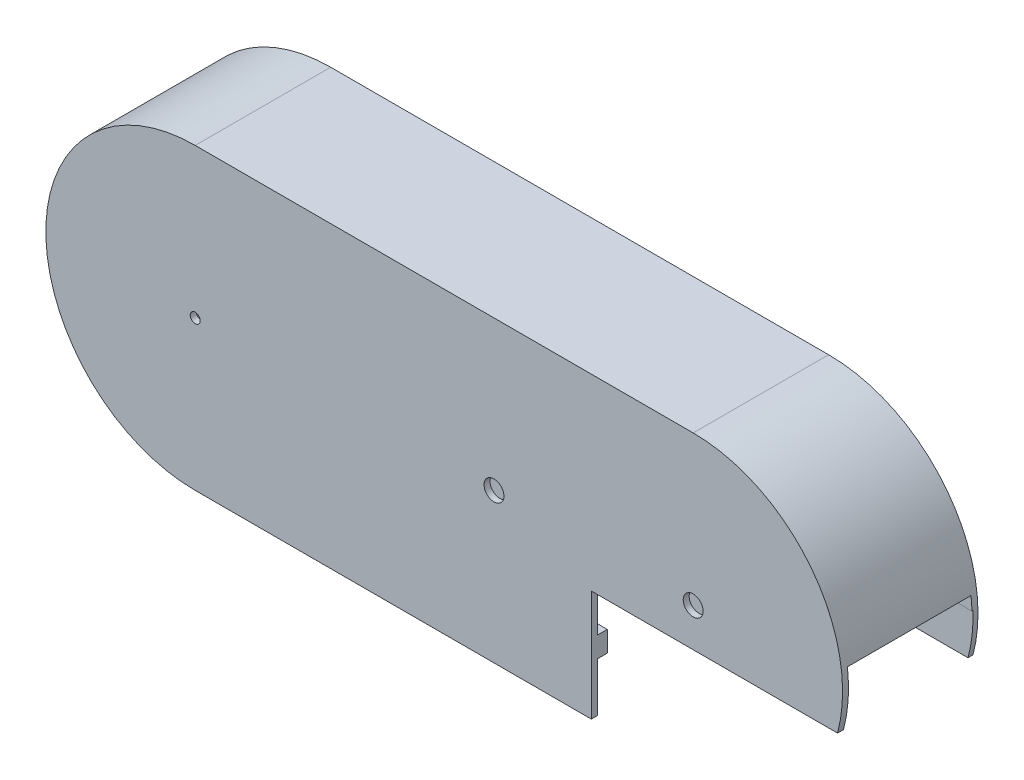
SolidWorks part; units mm, degrees
ref_plane "前视基准面" through (0, 0, 0) normal (0, 0, 1) x (1, 0, 0)
ref_plane "上视基准面" through (0, 0, 0) normal (0, 1, 0) x (1, 0, 0)
ref_plane "右视基准面" through (0, 0, 0) normal (1, 0, 0) x (0, 0, -1)
other "Configuration Table"
sketch "草图1" plane through (0, 0, 0) normal (0, 0, 1) x (1, 0, 0)
  line L0 (0, 0) -> (250, 0) construction
  line L1 (0, 75) -> (250, 75)
  line L2 (0, -75) -> (250, -75)
  arc A0 (0, 75) -> (0, -75) centre (0, 0) ccw
  arc A1 (250, -75) -> (250, 75) centre (250, 0) ccw
  point P3 (125, 0)
  dimension "D2" = 75
  dimension "D1" = 250
extrude "凸台-拉伸1" add sketch "草图1" along normal blind 68
ref_plane "基准面1" through (0, 0, 65) normal (0, 0, 1) x (1, 0, 0)
sketch "草图2" plane through (0, 0, 65) normal (0, 0, 1) x (1, 0, 0)
  line L0 (0, 75) -> (0, -75)
  line L1 (0, 0) -> (250, 0) construction
  line L2 (0, 72) -> (250, 72)
  line L3 (0, -72) -> (250, -72)
  arc A0 (0, 72) -> (0, -72) centre (0, 0) ccw
  arc A1 (250, -72) -> (250, 72) centre (250, 0) ccw
  point P7 (125, 0)
  dimension "D2" = 72
  dimension "D1" = 250
extrude "切除-拉伸2" cut sketch "草图2" against normal blind 62
ref_plane "基准面2" through (0, -75, 0) normal (0, -1, 0) x (-1, 0, 0)
sketch "草图3" plane through (0, -75, 0) normal (0, -1, 0) x (-1, 0, 0)
  line L0 (-82.5, -65) -> (82.5, -65) construction
  line L1 (-250, 0) -> (0, 0)
  line L2 (-250, 0) -> (-250, -65)
  line L3 (-250, -65) -> (0, -65)
  line L4 (0, 0) -> (0, -65)
  line L5 (0, -68) -> (0, 0) construction
extrude "切除-拉伸3" cut sketch "草图3" against normal blind 3
sketch "草图4" plane through (0, 0, 65) normal (0, 0, 1) x (1, 0, 0)
  line L0 (0, 75) -> (0, -75)
  line L1 (-1.65, -75) -> (1.65, -75) construction
  circle A0 centre (0, 0) radius 2.5
  dimension "D1" = 5
extrude "切除-拉伸5" cut sketch "草图4" against normal through all both and the other way through all contours L0 A0 | L0 A0
sketch "草图5" plane through (0, 0, 65) normal (0, 0, 1) x (1, 0, 0)
  line L1 (61.3786, 0) -> (220.7131, 0) construction
  line L2 (250, 75) -> (250, -75) construction
  line L3 (-1.65, -75) -> (1.65, -75) construction
  arc A0 (250, -75) -> (250, 75) centre (250, 0) ccw construction
  circle A1 centre (250, 0) radius 5
  circle A2 centre (150, 0) radius 5
  dimension "D1" = 10
  dimension "D2" = 10
  dimension "D3" = 100
extrude "切除-拉伸6" cut sketch "草图5" against normal through all both and the other way through all contours A2 | A1
ref_plane "基准面3" through (325, 0, 0) normal (1, 0, 0) x (0, 0, -1)
sketch "草图6" plane through (325, 0, 0) normal (1, 0, 0) x (0, 0, -1)
  line L0 (-68, 2.5) -> (0, 2.5) construction
  line L1 (-65, 2.5) -> (-65, -75)
  line L2 (-65, 82.5) -> (-65, -82.5) construction
  line L3 (-1.65, -75) -> (1.65, -75) construction
  line L4 (-65, -75) -> (-2.5, -75)
  line L5 (0, -75) -> (-65, -75) construction
  line L6 (-2.5, -75) -> (-2.5, 2.5)
  line L7 (-2.5, 2.5) -> (-65, 2.5)
  line L8 (0, -75) -> (0, 75) construction
  line L9 (0, -9.0022) -> (0, -54.0877) construction
  dimension "D1" = 5
extrude "切除-拉伸7" cut sketch "草图6" against normal blind 80
sketch "草图7" plane through (0, 0, 65) normal (0, 0, 1) x (1, 0, 0)
  line L0 (322.478, -19.2859) -> (198.8603, -19.2859)
  line L1 (198.8603, -19.2859) -> (198.8603, -75)
  line L2 (-1.65, -75) -> (1.65, -75) construction
  line L3 (198.8603, -75) -> (322.478, -75)
  line L4 (322.478, -75) -> (322.478, -19.2859)
  arc A0 (250, -75) -> (250, 75) centre (250, 0) ccw construction
extrude "切除-拉伸8" cut sketch "草图7" against normal through all both and the other way through all contours L3 L4 L0 L1
ref_plane "基准面4" through (0, 0, 65) normal (0, 0, -1) x (-1, 0, 0)
sketch "草图8" plane through (0, 0, 65) normal (0, 0, -1) x (-1, 0, 0)
  line L0 (49.472, 0) -> (-96.9567, 0) construction
  circle A0 centre (-32.64, 0) radius 5
  dimension "D2" = 10
  dimension "D1" = 32.64
extrude "凸台-拉伸2" add sketch "草图8" along normal blind 6
ref_plane "基准面5" through (0, 0, 3) normal (0, 0, 1) x (1, 0, 0)
sketch "草图9" plane through (0, 0, 3) normal (0, 0, 1) x (1, 0, 0)
  line L0 (0, 0) -> (127.487, 0)
  circle A0 centre (32.64, 0) radius 5
  dimension "D2" = 10
  dimension "D1" = 32.64
extrude "凸台-拉伸3" add sketch "草图9" along normal blind 6 contours L0 A0 | L0 A0
sketch "草图10" plane through (0, 0, 3) normal (0, 0, 1) x (1, 0, 0)
  line L0 (-52.2883, 53.7674) -> (302.2883, 53.7674)
  line L1 (-58.7241, 46.6528) -> (309.4619, 45.7086)
  line L2 (-63.455, -39.9808) -> (198.8603, -39.9808)
  line L3 (198.8603, -19.2859) -> (198.8603, -75) construction
  line L4 (-55.6036, -50.3313) -> (198.8603, -50.3313)
  line L5 (198.8603, -39.9808) -> (198.8603, -50.3313)
  arc A0 (0, 75) -> (0, -75) centre (0, 0) ccw construction
  arc A1 (322.478, -19.2859) -> (250, 75) centre (250, 0) ccw construction
  spline S0 degree 1 poles (-52.2883, 53.7674) (-58.7241, 46.6528) knots 0 0 1 1
  spline S1 degree 1 poles (302.2883, 53.7674) (309.4619, 45.7086) knots 0 0 1 1
  spline S2 degree 1 poles (-63.455, -39.9808) (-55.6036, -50.3313) knots 0 0 1 1
extrude "凸台-拉伸4" add sketch "草图10" along normal blind 5
pattern_linear "阵列(线性)1" count 2 spacing 57 along (0, 0, 1) of "凸台-拉伸4"
sketch "草图12" plane through (325, 0, 0) normal (1, 0, 0) x (0, 0, -1)
  line L0 (-65, 82.5) -> (-65, -82.5) construction
  line L1 (-65, 9.0242) -> (-3, 9.0242)
  line L2 (-65, 9.0242) -> (-65, 0)
  line L3 (-65, 0) -> (-3, 0)
  line L4 (-3, 9.0242) -> (-3, 0)
  line L5 (-3, 47.643) -> (-3, -47.643) construction
extrude "切除-拉伸9" cut sketch "草图12" against normal blind 10
